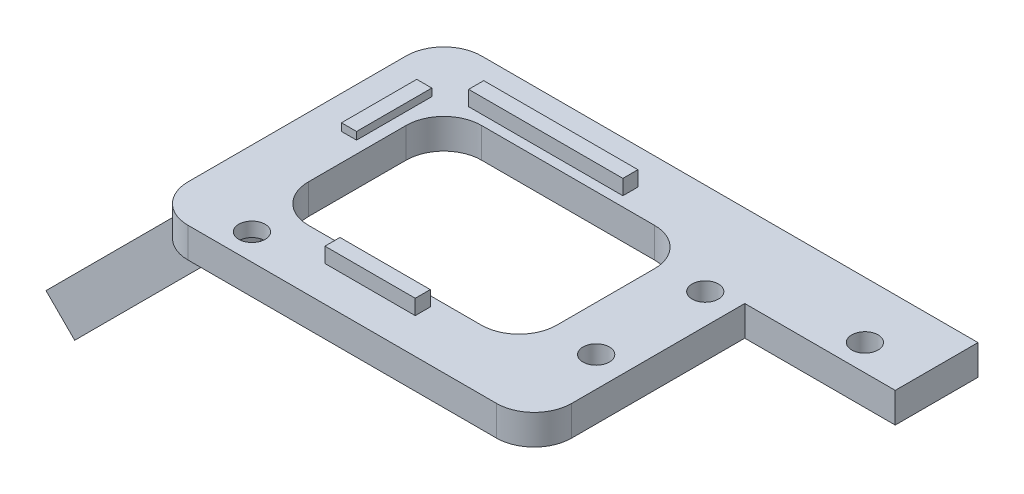
SolidWorks part; units mm, degrees
ref_plane "Front Plane" through (0, 0, 0) normal (0, 0, 1) x (1, 0, 0)
ref_plane "Top Plane" through (0, 0, 0) normal (0, 1, 0) x (1, 0, 0)
ref_plane "Right Plane" through (0, 0, 0) normal (1, 0, 0) x (0, 0, -1)
sketch "Sketch1" plane through (0, 0, 0) normal (0, 1, 0) x (1, 0, 0)
  line L0 (-16.5, 0) -> (16.5, 0) construction
  line L1 (16.5, -11.5) -> (-16.5, -11.5)
  line L2 (16.5, -11.5) -> (16.5, 11.5)
  line L3 (16.5, 11.5) -> (-16.5, 11.5)
  line L4 (-16.5, -11.5) -> (-16.5, 11.5)
  line L5 (16.5, -11.5) -> (-16.5, 11.5) construction
  line L6 (16.5, 11.5) -> (-16.5, -11.5) construction
  line L7 (26.5, -19.5) -> (-24.5, -19.5)
  line L8 (26.5, -19.5) -> (26.5, 19.5)
  line L9 (26.5, 19.5) -> (-24.5, 19.5)
  line L10 (-24.5, -19.5) -> (-24.5, 19.5)
  line L13 (0, 11.5) -> (0, -11.5) construction
  circle A0 centre (22.5, 7.25) radius 1.75
  circle A1 centre (22.5, -7.25) radius 1.75
  circle A2 centre (-14.5, -16) radius 1.75
  point P0 (0, 0)
  point P6 (0, 0)
  point P21 (-24.5, 0)
  dimension "D5" = 3.5
  dimension "D7" = 14.5
  dimension "D1" = 33
  dimension "D2" = 23
  dimension "D3" = 39
  dimension "D4" = 10
  dimension "D6" = 4
  dimension "D8" = 4.5
  dimension "D9" = 8
  dimension "D10" = 10
extrude "Boss-Extrude1" add sketch "Sketch1" along normal blind 4
fillet "Fillet1" radius 5 4 edges at (-16.5, 2, 11.5) (16.5, 2, 11.5) (16.5, 2, -11.5) (-16.5, 2, -11.5)
sketch "Sketch2" plane through (0, 4, 0) normal (0, 1, 0) x (1, 0, 0)
  line L10 (-14.5, 14.8) -> (6, 14.8)
  line L16 (-14.5, 14.8) -> (-14.5, 12.8)
  line L17 (-14.5, 12.8) -> (6, 12.8)
  line L24 (0, 11.5) -> (0, -11.5) construction
  line L25 (11.5, 11.5) -> (-11.5, 11.5) construction
  line L26 (-11.5, -11.5) -> (11.5, -11.5) construction
  line L27 (-16.5, 0) -> (16.5, 0) construction
  line L28 (-16.5, 6.5) -> (-16.5, -6.5) construction
  line L29 (16.5, -6.5) -> (16.5, 6.5) construction
  line L38 (6, 14.8) -> (6, 12.8)
  line L43 (-6, -12.8) -> (6, -12.8)
  line L44 (-6, -12.8) -> (-6, -14.8)
  line L45 (-6, -14.8) -> (6, -14.8)
  line L46 (6, -12.8) -> (6, -14.8)
  dimension "D1" = 2
  dimension "D2" = 14.5
  dimension "D3" = 12.8
  dimension "D4" = 12.8
  dimension "D5" = 6
  dimension "D6" = 12
extrude "Boss-Extrude4" add sketch "Sketch2" along normal blind 2
fillet "Fillet5" radius 5 4 edges at (-24.5, 2, 19.5) (26.5, 2, 19.5) (26.5, 2, -19.5) (-24.5, 2, -19.5)
sketch "Sketch4" plane through (0, 0, 0) normal (0, -1, 0) x (1, 0, 0)
  line L1 (-12.8546, 13.15) -> (-11.2091, 16)
  line L2 (-11.2091, 16) -> (-12.8546, 18.85)
  line L3 (-12.8546, 18.85) -> (-16.1454, 18.85)
  line L4 (-16.1454, 18.85) -> (-17.7909, 16)
  line L5 (-17.7909, 16) -> (-16.1454, 13.15)
  line L6 (-16.1454, 13.15) -> (-12.8546, 13.15)
  circle A0 centre (-14.5, 16) radius 2.85 construction
  dimension "D1" = 5.7
extrude "Cut-Extrude1" cut sketch "Sketch4" against normal blind 2.1
sketch "Sketch5" plane through (0, 4, 0) normal (0, 1, 0) x (1, 0, 0)
  line L0 (11.5, 11.5) -> (-11.5, 11.5) construction
  line L1 (-20.1, 11.5) -> (-18.1, 11.5)
  line L2 (-20.1, 11.5) -> (-20.1, 1.5)
  line L3 (-20.1, 1.5) -> (-18.1, 1.5)
  line L4 (-18.1, 11.5) -> (-18.1, 1.5)
  dimension "D1" = 10
  dimension "D2" = 2
  dimension "D3" = 18.1
extrude "Boss-Extrude5" add sketch "Sketch5" along normal blind 1
sketch "Sketch6" plane through (0, 0, 0) normal (0, 0, 1) x (1, 0, 0)
  line L3 (-50.8758, -25.4558) -> (-25.42, 0)
  line L4 (-25.42, 0) -> (-17.7909, 0)
  line L5 (-17.7909, 0) -> (-47.0613, -29.2704)
  line L7 (-50.8758, -25.4558) -> (-47.0613, -29.2704)
  line L8 (-24.5, 0) -> (-24.5, 4) construction
  dimension "D1" = 36
  dimension "D2" = 135
  dimension "D3" = 0.92
extrude "Boss-Extrude6" add sketch "Sketch6" along normal blind 7 and the other way blind 7
sketch "Sketch7" plane through (-8.8954, 8.8954, 0) normal (0.7071, -0.7071, 0) x (0, 0, -1)
  line L0 (7, -53.9747) -> (-7, -53.9747) construction
  circle A0 centre (0, -45.9747) radius 1.75
  point P4 (0, -53.9747)
  dimension "D1" = 3.5
  dimension "D2" = 8
extrude "Cut-Extrude2" cut sketch "Sketch7" against normal up to surface (5.3946 mm away) up to face at (-38.1479, -12.7279, 0)
sketch "Sketch8" plane through (-8.8954, 8.8954, 0) normal (0.7071, -0.7071, 0) x (0, 0, -1)
  line L0 (7, -12.5801) -> (33.1547, -48.7133)
  line L2 (25.0542, -54.5768) -> (7, -29.6346)
  line L3 (7, -53.9747) -> (7, -12.5801) construction
  line L4 (7, -29.6346) -> (7, -12.5801)
  line L5 (25, -45.9747) -> (20.9497, -48.9064) construction
  line L6 (25, -45.9747) -> (29.0503, -43.0429) construction
  line L8 (25.0542, -54.5768) -> (33.1547, -48.7133)
  line L9 (25, -45.9747) -> (29.1045, -51.645) construction
  circle A0 centre (25, -45.9747) radius 1.75
  circle A1 centre (0, -45.9747) radius 1.75 construction
  circle A2 centre (0, -45.9747) radius 1.75 construction
  dimension "D1" = 5
  dimension "D2" = 25
  dimension "D3" = 7
extrude "Boss-Extrude7" add sketch "Sketch8" against normal up to surface (5.3946 mm away) up to face at (-46.4564, -21.0364, 0)
sketch "Sketch10" plane through (26.5, 0, 0) normal (1, 0, 0) x (0, 0, -1)
  line L0 (-14.5, 4) -> (14.5, 4) construction
  line L1 (8.5, 4) -> (19.5, 4)
  line L2 (8.5, 4) -> (8.5, 0)
  line L3 (8.5, 0) -> (19.5, 0)
  line L4 (19.5, 4) -> (19.5, 0)
  dimension "D1" = 11
extrude "Boss-Extrude9" add sketch "Sketch10" along normal blind 20 and the other way up to surface other way up to face at (24.5178, 2, -17.5178)
sketch "Sketch11" plane through (0, 4, 0) normal (0, 1, 0) x (1, 0, 0)
  line L0 (46.5, 19.5) -> (46.5, 8.5) construction
  line L1 (46.5, 19.5) -> (-19.5, 19.5) construction
  circle A2 centre (38.97, 12) radius 1.75
  dimension "D2" = 7.53
  dimension "D1" = 3.5
  dimension "D3" = 7.5
extrude "Cut-Extrude3" cut sketch "Sketch11" against normal up to surface (4 mm away) up to face at (22.5, 0, 5.5)
ref_plane "Plane1" through (0, 0, 0) normal (-0.7071, 0.7071, 0) x (0.7071, 0.7071, 0)
ref_plane "Plane2" through (0, 0, 0) normal (0.7071, 0.7071, 0) x (0.7071, -0.7071, 0)
sketch "Sketch12" plane through (0, 0, 0) normal (0, -1, 0) x (1, 0, 0)
  line L0 (-19.5, 19.5) -> (21.5, 19.5) construction
  line L1 (16.5, 23.5) -> (36.5, 23.5)
  line L2 (16.5, 23.5) -> (16.5, 15.5)
  line L3 (16.5, 15.5) -> (36.5, 15.5)
  line L4 (36.5, 23.5) -> (36.5, 15.5)
  line L5 (26.5, 14.5) -> (26.5, -8.5) construction
  point P6 (16.5, 19.5)
  dimension "D1" = 4
  dimension "D2" = 20
  dimension "D3" = 10
extrude "Cut-Extrude4" [suppressed] cut sketch "Sketch12" against normal up to surface (4 mm away)
ref_plane "Plane3" through (10.25, 10.25, 0) normal (0.7071, 0.7071, 0) x (0.7071, -0.7071, 0)
sketch "Sketch13" plane through (10.25, 10.25, 0) normal (0.7071, 0.7071, 0) x (0.7071, -0.7071, 0)
  line L0 (8.8388, -6.5) -> (8.8388, 6.5) construction
  line L1 (8.8388, -6.5) -> (8.8388, 11.5)
  line L4 (-8.1317, -11.5) -> (8.1317, -11.5) construction
  line L5 (8.8388, -6.5) -> (8.8388, -11.5)
  line L6 (8.8388, -11.5) -> (14.8907, -11.5)
  line L7 (14.8907, -11.5) -> (14.8907, 11.5)
  line L8 (14.8907, 11.5) -> (8.8388, 11.5)
  line L9 (8.1317, 11.5) -> (-8.1317, 11.5) construction
